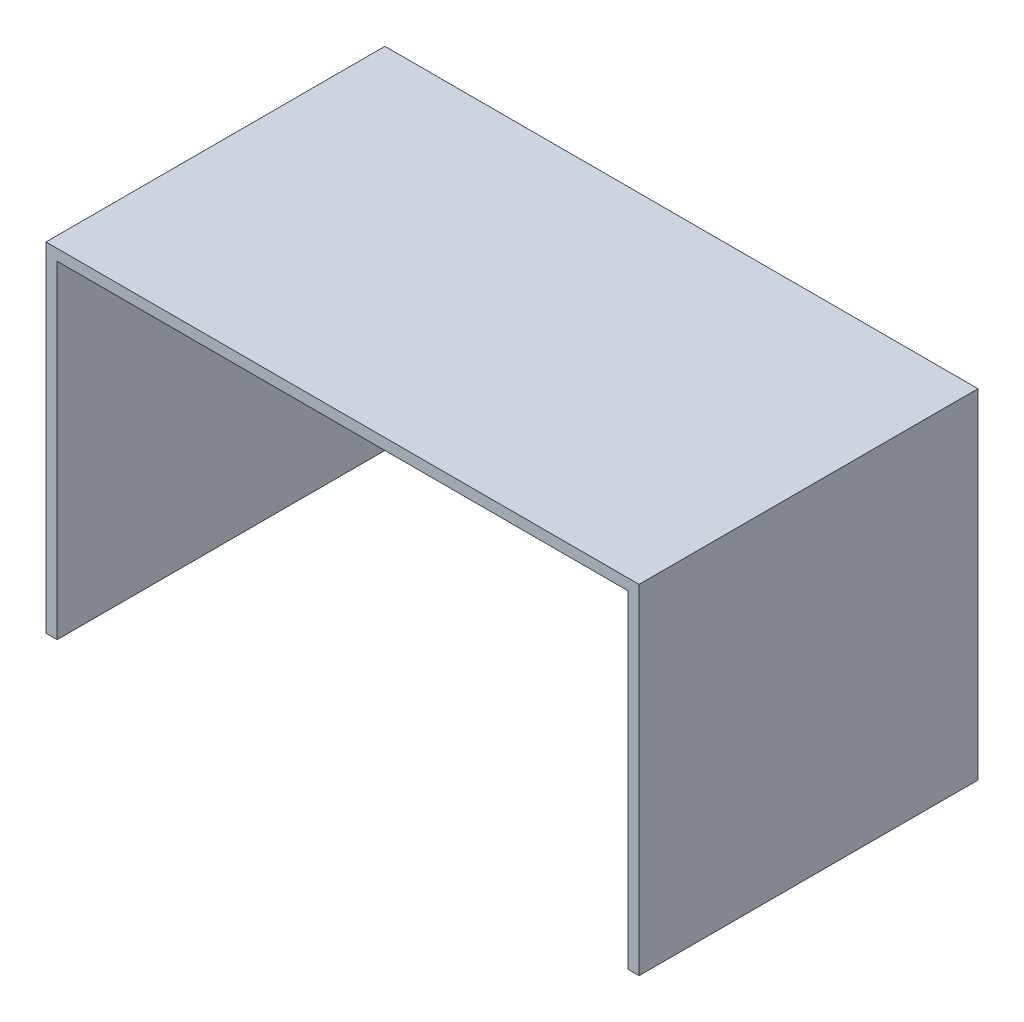
SolidWorks part; units mm, degrees
ref_plane "Front Plane" through (0, 0, 0) normal (0, 0, 1) x (1, 0, 0)
ref_plane "Top Plane" through (0, 0, 0) normal (0, 1, 0) x (1, 0, 0)
ref_plane "Right Plane" through (0, 0, 0) normal (1, 0, 0) x (0, 0, -1)
sketch "Sketch1" plane through (0, 0, 0) normal (0, 0, 1) x (1, 0, 0)
  line L1 (-0.2667, -0.1524) -> (0.2667, -0.1524)
  line L2 (-0.2667, -0.1524) -> (-0.2667, 0.1524)
  line L3 (-0.2667, 0.1524) -> (0.2667, 0.1524)
  line L4 (0.2667, -0.1524) -> (0.2667, 0.1524)
  line L5 (-0.2667, -0.1524) -> (0.2667, 0.1524) construction
  line L6 (-0.2667, 0.1524) -> (0.2667, -0.1524) construction
  point P0 (0, 0)
  dimension "D1" = 0.5334
  dimension "D2" = 0.3048
extrude "Boss-Extrude1" add sketch "Sketch1" along normal mid plane 0.3048
sketch "Sketch2" plane through (0, 0, 0.1524) normal (0, 0, 1) x (1, 0, 0)
  line L0 (-0.2667, -0.1524) -> (0.2667, -0.1524) construction
  line L1 (-0.2567, 0.1424) -> (0.2567, 0.1424)
  line L2 (-0.2567, 0.1424) -> (-0.2567, -0.1524)
  line L3 (-0.2567, -0.1524) -> (0.2567, -0.1524)
  line L4 (0.2567, 0.1424) -> (0.2567, -0.1524)
  line L5 (-0.2567, -0.005) -> (-0.2667, -0.005) construction
  line L6 (-0.2667, 0.1524) -> (-0.2667, -0.1524) construction
  line L7 (0, 0.1424) -> (0, 0.1524) construction
  line L8 (0.2667, 0.1524) -> (-0.2667, 0.1524) construction
  line L9 (0.2567, -0.005) -> (0.2667, -0.005) construction
  line L10 (0.2667, -0.1524) -> (0.2667, 0.1524) construction
  dimension "D1" = 0.01
extrude "Cut-Extrude1" cut sketch "Sketch2" against normal offset from surface (0.2948 mm away) 0.01 up to face at (0, 0, -0.1524)
